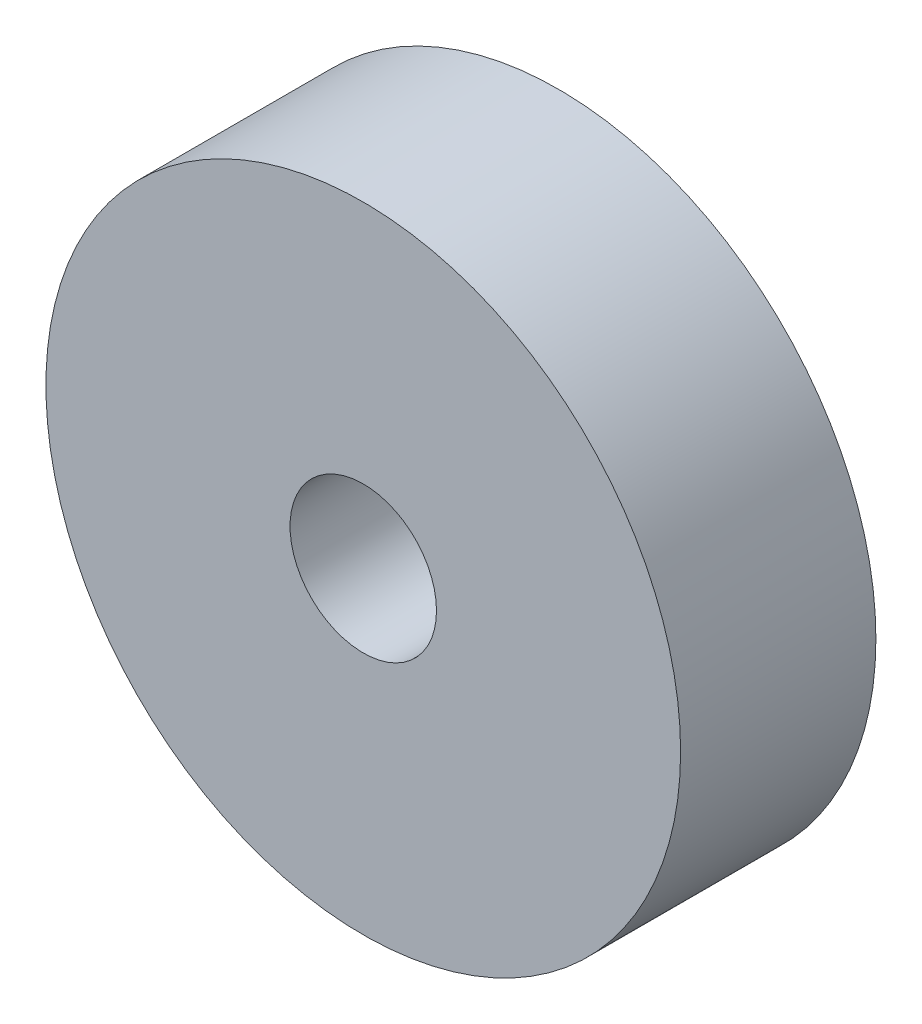
SolidWorks part; units mm, degrees
ref_plane "正面" through (0, 0, 0) normal (1, 0, 0) x (0, 1, 0)
ref_plane "平面" through (0, 0, 0) normal (0, 0, 1) x (0, 1, 0)
ref_plane "右側面" through (0, 0, 0) normal (0, 1, 0) x (-1, 0, 0)
sketch "ｽｹｯﾁ1" plane through (0, 0, 0) normal (0, 0, 1) x (0, 1, 0)
  circle A0 centre (0, 0) radius 3.25
  circle A1 centre (0, 0) radius 0.75
  dimension "D1" = 6.5
  dimension "D2" = 1.5
extrude "ﾎﾞｽ - 押し出し1" add sketch "ｽｹｯﾁ1" along normal blind 2 contours A1 | A0
